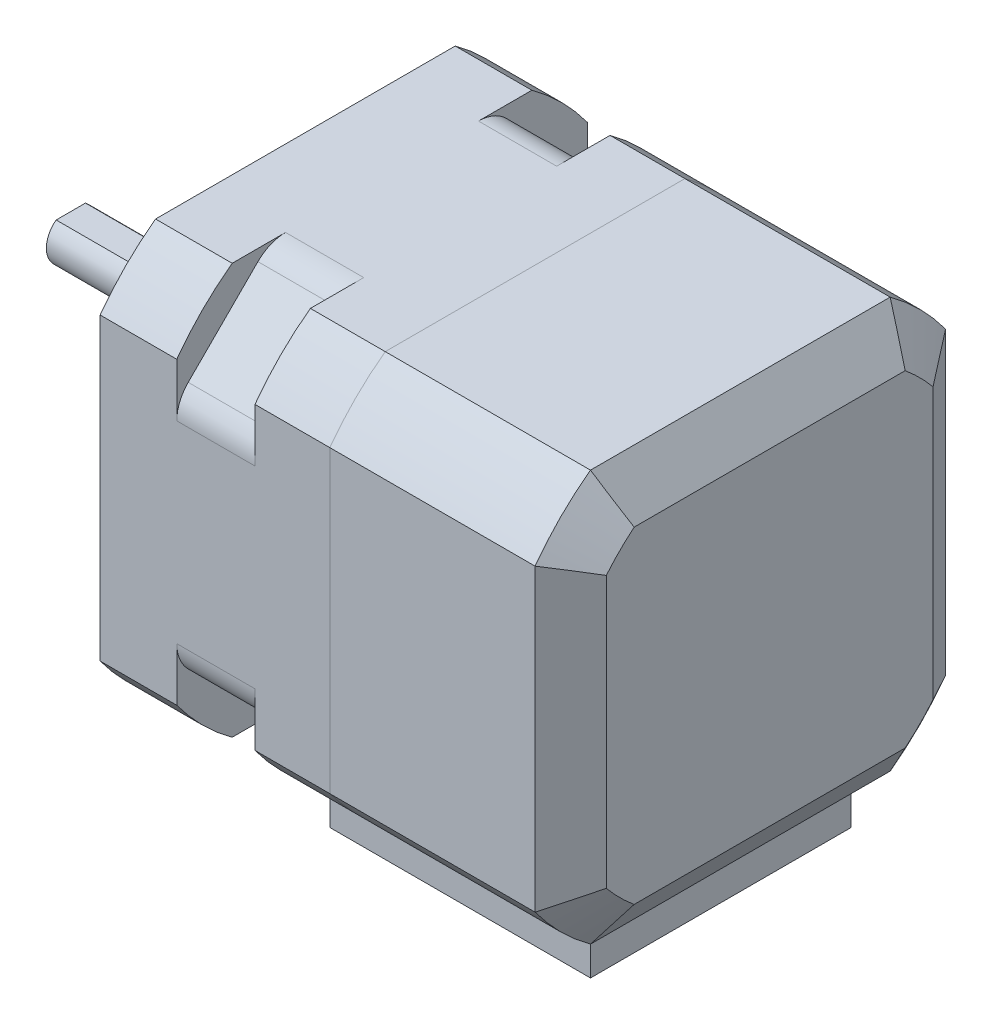
SolidWorks part; units mm, degrees
material "Aluminium"
ref_plane "Plan XY" through (0, 0, 0) normal (0, 0, 1) x (1, 0, 0)
ref_plane "Plan ZX" through (0, 0, 0) normal (0, 1, 0) x (1, 0, 0)
ref_plane "Plan YZ" through (0, 0, 0) normal (1, 0, 0) x (0, 0, -1)
sketch "Esquisse1" plane through (0, 0, 0) normal (1, 0, 0) x (0, 0, -1)
  line L1 (21, -21) -> (-21, -21)
  line L2 (21, -21) -> (21, 21)
  line L3 (21, 21) -> (-21, 21)
  line L4 (-21, -21) -> (-21, 21)
  line L5 (21, -21) -> (-21, 21) construction
  line L6 (21, 21) -> (-21, -21) construction
  point P0 (0, 0)
  dimension "D1" = 42
extrude "Boss.-Extru.1" add sketch "Esquisse1" along normal blind 47.5
sketch "Esquisse2" plane through (0, 0, 0) normal (1, 0, 0) x (0, 0, -1)
  circle A0 centre (0, 0) radius 11
  dimension "D1" = 22
extrude "Boss.-Extru.2" add sketch "Esquisse2" against normal blind 2
sketch "Esquisse3" plane through (0, 0, 0) normal (-1, 0, 0) x (0, 0, 1)
  circle A0 centre (0, 0) radius 2.5
  dimension "D1" = 5
extrude "Boss.-Extru.3" add sketch "Esquisse3" along normal blind 24
hole_wizard "Trou taraudé M31" positions "Esquisse4" profile "Esquisse5" tap size "M3" standard "ISO"
sketch "Esquisse4" plane through (0, 0, 0) normal (-1, 0, 0) x (0, 0, 1)
  line L1 (15.5, -15.5) -> (-15.5, -15.5) construction
  line L2 (15.5, -15.5) -> (15.5, 15.5) construction
  line L3 (15.5, 15.5) -> (-15.5, 15.5) construction
  line L4 (-15.5, -15.5) -> (-15.5, 15.5) construction
  line L5 (15.5, -15.5) -> (-15.5, 15.5) construction
  line L6 (15.5, 15.5) -> (-15.5, -15.5) construction
  point P0 (-15.5, 15.5)
  point P2 (15.5, 15.5)
  point P4 (-15.5, -15.5)
  point P6 (15.5, -15.5)
  dimension "D1" = 31
sketch "Esquisse5" plane through (0, 15.5, -15.5) normal (0, 1, 0) x (0, 0, 1)
  line L0 (0, 0) -> (0, 4.7511)
  line L1 (0, 4.7511) -> (1.25, 4)
  line L2 (1.25, 4) -> (1.25, 0)
  line L5 (1.25, 0) -> (0, 0)
  line L10 (0, 4.7511) -> (-1.25, 4) construction
  line L11 (0, -6.35) -> (0, 107.95) construction
  dimension "Diamètre du trou pour taraudage" = 2.5
  dimension "Profondeur du trou pour taraudage" = 4
  dimension "Angle de pointe" = 118
cosmetic thread "Filetage de perçage1" parameters "D1"=4, "D2"=3
cosmetic thread "Filetage de perçage2" parameters "D1"=4, "D2"=3
cosmetic thread "Filetage de perçage3" parameters "D1"=4, "D2"=3
cosmetic thread "Filetage de perçage4" parameters "D1"=4, "D2"=3
sketch "Esquisse6" plane through (0, 0, 0) normal (1, 0, 0) x (0, 0, -1)
  circle A0 centre (0, 0) radius 26
  dimension "D1" = 52
extrude "Enlèv. mat.-Extru.1" cut sketch "Esquisse6" along normal through all flip side to cut
sketch "Esquisse7" plane through (0, 0, 0) normal (0, 0, 1) x (1, 0, 0)
  line L0 (-24, 2) -> (-9, 2)
  line L1 (-24, 2.5) -> (-24, -2.5) construction
  line L2 (-9, 2) -> (-9, 2.5)
  line L3 (-2, 2.5) -> (-24, 2.5) construction
  line L4 (-24, -2.5) -> (-2, -2.5) construction
  dimension "D1" = 4.5
  dimension "D2" = 15
extrude "Enlèv. mat.-Extru.2" cut sketch "Esquisse7" against normal through all both and the other way through all
ref_plane "Plan1" through (23.5, 0, 0) normal (1, 0, 0) x (0, 0, -1)
split line "Ligne de séparation1"
chamfer "Chanfrein1" distance 3 angle 55 8 edges at (47.5, -21, 0) (47.5, -18.3848, 18.3848) (47.5, 0, 21) (47.5, 18.3848, 18.3848) (47.5, 21, 0) (47.5, 18.3848, -18.3848) (47.5, 0, -21) (47.5, -18.3848, -18.3848)
sketch "Esquisse10" plane through (0, -21, 0) normal (0, -1, 0) x (1, 0, 0)
  line L0 (23.5, 15.3297) -> (0, 15.3297) construction
  line L1 (44.5, -15.3297) -> (13.8406, -15.3297) construction
  line L2 (44.5, -15.3297) -> (44.5, 15.3297) construction
  line L3 (44.5, 15.3297) -> (13.8406, 15.3297) construction
  line L4 (13.8406, -15.3297) -> (13.8406, 15.3297) construction
  line L5 (42.5, -13.3297) -> (15.8406, -13.3297)
  line L6 (15.8406, -13.3297) -> (15.8406, 13.3297)
  line L7 (42.5, 13.3297) -> (15.8406, 13.3297)
  line L8 (42.5, -13.3297) -> (42.5, 13.3297)
  dimension "D1" = 2
extrude "Boss.-Extru.5" add sketch "Esquisse10" along normal blind 10
chamfer "Chanfrein2" distance 5 angle 45 3 edges at (29.1703, -31, 13.3297) (42.5, -31, 0) (29.1703, -31, -13.3297)
sketch "Esquisse11" plane through (15.8406, 0, 0) normal (-1, 0, 0) x (0, 0, 1)
  line L0 (0, 32.5269) -> (-32.5269, 0)
  line L1 (0, 32.5269) -> (32.5269, 0)
  line L2 (-32.5269, 0) -> (0, -32.5269)
  line L3 (32.5269, 0) -> (0, -32.5269)
  line L4 (-32.5269, 0) -> (0, 0) construction
  line L5 (0, 0) -> (0, 32.5269) construction
  line L6 (0, -32.5269) -> (0, 0) construction
  dimension "D1" = 46
extrude "Enlèv. mat.-Extru.3" cut sketch "Esquisse11" along normal blind 8 flip side to cut
fillet "Congé1" radius 4 8 edges at (11.8406, -21, 11.5269) (11.8406, -11.5269, 21) (11.8406, 11.5269, 21) (11.8406, 21, 11.5269) (11.8406, 21, -11.5269) (11.8406, 11.5269, -21) (11.8406, -21, -11.5269) (11.8406, -11.5269, -21)
